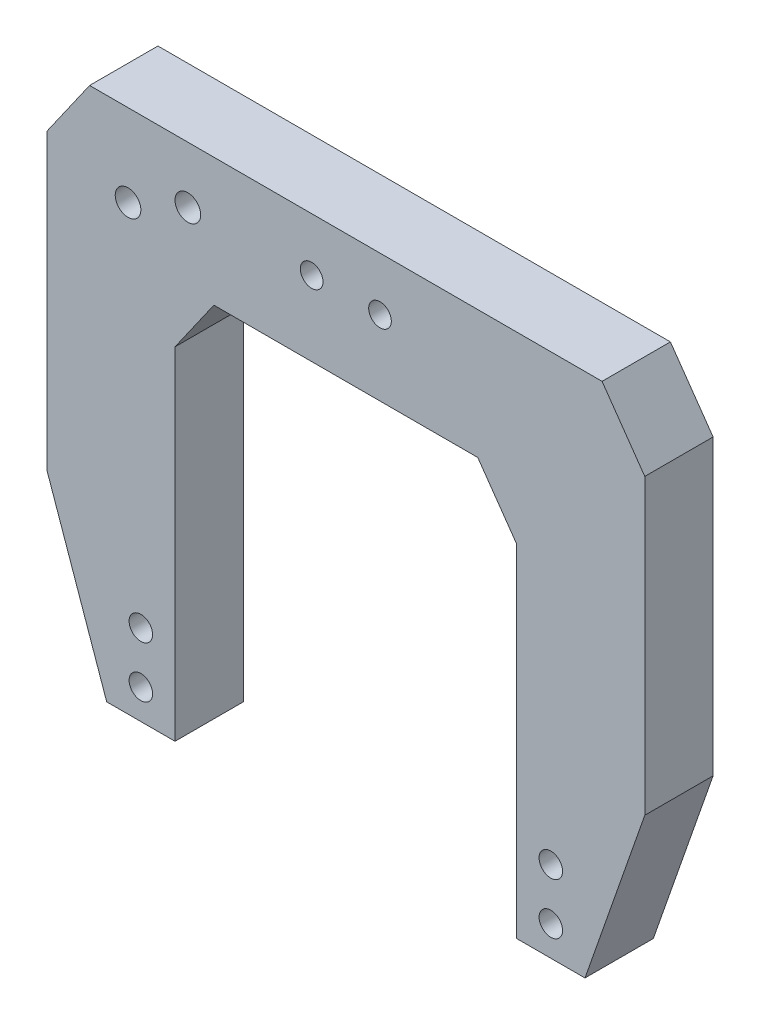
SolidWorks part; units mm, degrees
ref_plane "Płaszczyzna przednia" through (0, 0, 0) normal (0, 0, 1) x (1, 0, 0)
ref_plane "Płaszczyzna górna" through (0, 0, 0) normal (0, 1, 0) x (1, 0, 0)
ref_plane "Płaszczyzna prawa" through (0, 0, 0) normal (1, 0, 0) x (0, 0, -1)
sketch "Szkic1" plane through (0, 0, 0) normal (0, 0, 1) x (1, 0, 0)
  line L0 (0, 93) -> (0, 123)
  line L1 (0, 123) -> (60, 123)
  line L2 (60, 123) -> (70, 108.7185)
  line L3 (70, 108.7185) -> (70, 40)
  line L4 (56, 0) -> (40, 0)
  line L5 (40, 0) -> (40, 80)
  line L6 (40, 80) -> (30.8973, 93)
  line L7 (30.8973, 93) -> (0, 93)
  line L8 (56, 0) -> (70, 40)
  dimension "D1" = 30
  dimension "D2" = 30
  dimension "D3" = 93
  dimension "D4" = 40
  dimension "D5" = 145
  dimension "D6" = 80
  dimension "D7" = 145
  dimension "D8" = 16
  dimension "D9" = 40
  dimension "D10" = 60
extrude "Dodanie-wyciągnięcie1" add sketch "Szkic1" along normal mid plane 16
mirror "Lustro1" about plane through (0, 93, 8) normal (1, 0, 0) of "Dodanie-wyciągnięcie1"
hole_wizard "Pogłębienie walcowe pod M5 Śrubę z łbem walcowym z gniazdem2" positions "Szkic6" profile "Szkic7" counterbore size "M5" standard "Ansi Metric"
sketch "Szkic6" plane through (156.3495, 156, 18.4274) normal (0, 0, 1) x (1, 0, 0)
  line L1 (-133.3445, -57.5) -> (-179.3545, -57.5)
  line L2 (-133.3445, -57.5) -> (-179.3545, -57.5)
  point P0 (-164.3495, -45.5)
  point P2 (-148.3495, -45.5)
sketch "Szkic7" plane through (-8, 110.5, 18.4274) normal (1, 0, 0) x (0, -1, 0)
  line L0 (0, 0) -> (0, 61.5923)
  line L1 (0, 61.5923) -> (2.65, 60)
  line L2 (2.65, 60) -> (2.65, 2)
  line L3 (2.65, 2) -> (5, 2)
  line L4 (5, 2) -> (5, 0)
  line L5 (5, 0) -> (0, 0)
  line L6 (0, 61.5923) -> (-2.65, 60) construction
  line L7 (0, -6.35) -> (0, 107.95) construction
  dimension "Średnica otworu" = 5.3
  dimension "Głębokość otworu" = 60
  dimension "Średnica pogłębienia walcowego" = 10
  dimension "Głębokość pogłębienia walcowego" = 2
  dimension "Kąt wiertła" = 118
hole_wizard "Pogłębienie walcowe pod M5 Śrubę z łbem walcowym z gniazdem3" positions "Szkic8" profile "Szkic9" counterbore size "M5" standard "Ansi Metric"
sketch "Szkic8" plane through (156.3495, 156, -22) normal (0, 0, -1) x (-1, 0, 0)
  line L1 (197.3495, -176) -> (211.3495, -176) construction
  point P0 (204.3495, -149)
  point P2 (204.3495, -137)
sketch "Szkic9" plane through (-48, 7, -22) normal (1, 0, 0) x (0, 1, 0)
  line L0 (0, 0) -> (0, 45.6524)
  line L1 (0, 45.6524) -> (2.75, 44)
  line L2 (2.75, 44) -> (2.75, 5)
  line L3 (2.75, 5) -> (5, 5)
  line L4 (5, 5) -> (5, 0)
  line L5 (5, 0) -> (0, 0)
  line L6 (0, 45.6524) -> (-2.75, 44) construction
  line L7 (0, -6.35) -> (0, 107.95) construction
  dimension "Średnica otworu" = 5.5
  dimension "Głębokość otworu" = 44
  dimension "Średnica pogłębienia walcowego" = 10
  dimension "Głębokość pogłębienia walcowego" = 5
  dimension "Kąt wiertła" = 118
mirror "Lustro2" about plane through (0, 0, 0) normal (1, 0, 0) of "Pogłębienie walcowe pod M5 Śrubę z łbem walcowym z gniazdem3"
hole_wizard "Otwory ustalające Ø6.0mm1" positions "Szkic10" profile "Szkic11" hole size "Ø6.0" standard "Ansi Metric"
sketch "Szkic10" plane through (156.3495, 156, 8) normal (0, 0, 1) x (1, 0, 0)
  line L3 (-185.3495, -41.25) -> (-215.3495, -41.25)
  line L5 (-215.3495, -57.25) -> (-215.3495, -41.25)
  point P0 (-193.3495, -46.25)
  point P2 (-207.3495, -52.25)
sketch "Szkic11" plane through (-37, 109.75, 8) normal (1, 0, 0) x (0, -1, 0)
  line L0 (0, 0) -> (0, 33.8026)
  line L1 (0, 33.8026) -> (3, 32)
  line L2 (3, 32) -> (3, 0)
  line L3 (3, 0) -> (0, 0)
  line L4 (0, 33.8026) -> (-3, 32) construction
  line L5 (0, -6.35) -> (0, 107.95) construction
  dimension "Średnica otworu" = 6
  dimension "Głębokość otworu" = 32
  dimension "Kąt wiertła" = 118
